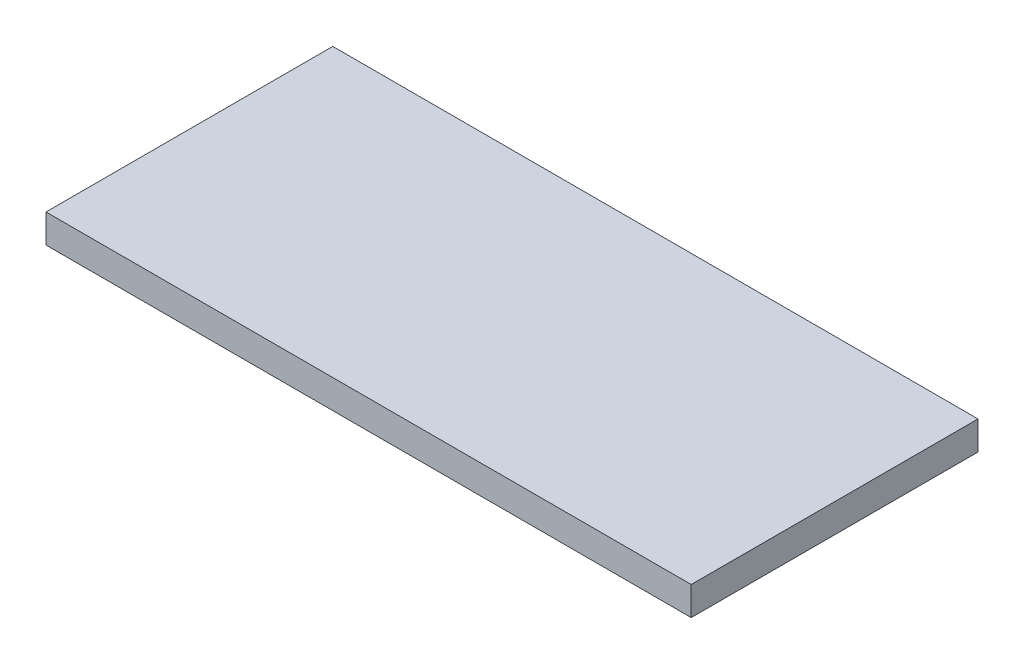
SolidWorks part; units mm, degrees
ref_plane "Front Plane" through (0, 0, 0) normal (0, 0, 1) x (1, 0, 0)
ref_plane "Top Plane" through (0, 0, 0) normal (0, 1, 0) x (1, 0, 0)
ref_plane "Right Plane" through (0, 0, 0) normal (1, 0, 0) x (0, 0, -1)
sketch "Sketch1" plane through (0, 0, 0) normal (0, 1, 0) x (1, 0, 0)
  line L1 (-90, 40) -> (90, 40)
  line L2 (-90, 40) -> (-90, -40)
  line L3 (-90, -40) -> (90, -40)
  line L4 (90, 40) -> (90, -40)
  point P4 (0, 40)
  point P6 (90, 0)
  dimension "D1" = 180
  dimension "D2" = 80
extrude "Boss-Extrude1" add sketch "Sketch1" along normal blind 8
